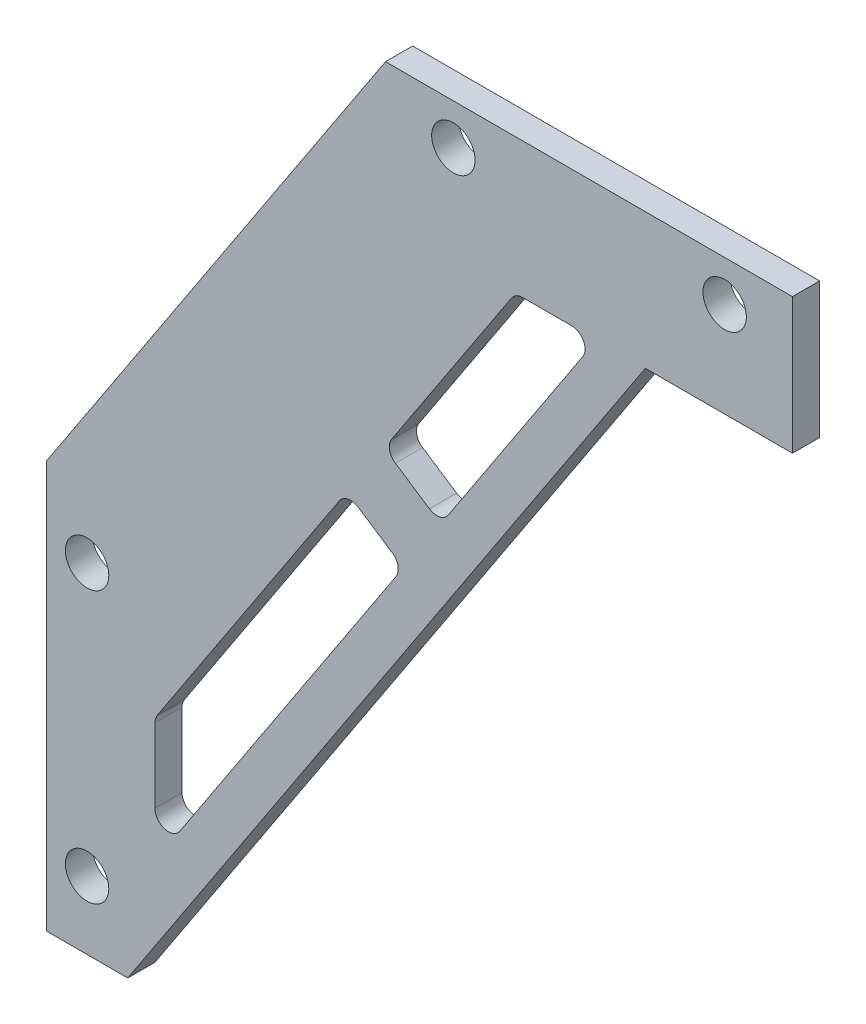
SolidWorks part; units mm, degrees
material "Thornel Mat VMA"
ref_plane "前视基准面" through (0, 0, 0) normal (0, 0, 1) x (1, 0, 0)
ref_plane "上视基准面" through (0, 0, 0) normal (0, 1, 0) x (1, 0, 0)
ref_plane "右视基准面" through (0, 0, 0) normal (1, 0, 0) x (0, 0, -1)
sketch "草图1" plane through (0, 0, 0) normal (0, 0, 1) x (1, 0, 0)
  line L0 (0, 0) -> (0, 30)
  line L1 (0, 30) -> (25, 68)
  line L2 (25, 68) -> (55, 68)
  line L3 (55, 68) -> (55, 58)
  line L4 (55, 58) -> (44.1579, 58)
  line L5 (44.1579, 58) -> (6, 0)
  line L6 (6, 0) -> (0, 0)
  line L7 (3, 25) -> (3, 5) construction
  line L8 (30, 65) -> (50, 65) construction
  circle A0 centre (3, 25) radius 1.6
  circle A1 centre (3, 5) radius 1.6
  circle A2 centre (30, 65) radius 1.6
  circle A3 centre (50, 65) radius 1.6
  dimension "D4" = 20
  dimension "D7" = 3.2
  dimension "D11" = 3.2
  dimension "D1" = 30
  dimension "D2" = 6
  dimension "D3" = 10
  dimension "D5" = 3
  dimension "D6" = 5
  dimension "D8" = 25
  dimension "D9" = 38
  dimension "D10" = 30
  dimension "D12" = 5
  dimension "D13" = 5
  dimension "D14" = 3
extrude "凸台-拉伸1" add sketch "草图1" along normal blind 2
sketch "草图2" plane through (0, 0, 2) normal (0, 0, 1) x (1, 0, 0)
  line L0 (35.121, 58) -> (38.712, 58)
  line L1 (39.5474, 56.4504) -> (29.6216, 41.3632)
  line L2 (8, 11.8378) -> (8, 17.2962)
  line L3 (8.1646, 17.8458) -> (21.5972, 38.2634)
  line L4 (6, 0) -> (44.1579, 58) construction
  line L5 (25.7303, 42.7262) -> (28.2366, 41.0774)
  line L6 (22.9822, 38.5492) -> (25.4885, 36.9003)
  line L7 (25.4445, 44.1113) -> (34.2855, 57.5496)
  line L8 (25.7743, 35.5153) -> (9.8354, 11.2882)
  line L9 (0, 30) -> (0, 0) construction
  arc A0 (38.712, 58) -> (39.5474, 56.4504) centre (38.712, 57) cw
  arc A1 (35.121, 58) -> (34.2855, 57.5496) centre (35.121, 57) ccw
  arc A2 (8, 17.2962) -> (8.1646, 17.8458) centre (9, 17.2962) cw
  arc A3 (9.8354, 11.2882) -> (8, 11.8378) centre (9, 11.8378) cw
  arc A4 (28.2366, 41.0774) -> (29.6216, 41.3632) centre (28.7862, 41.9128) ccw
  arc A5 (25.7303, 42.7262) -> (25.4445, 44.1113) centre (26.2799, 43.5617) cw
  arc A6 (25.4885, 36.9003) -> (25.7743, 35.5153) centre (24.9389, 36.0649) cw
  arc A7 (22.9822, 38.5492) -> (21.5972, 38.2634) centre (22.4326, 37.7137) ccw
  point P24 (24.8949, 43.2759)
  point P27 (26.3239, 36.3507)
  dimension "D3" = 1
  dimension "D6" = 1
  dimension "D1" = 3
  dimension "D2" = 5
  dimension "D4" = 5
  dimension "D5" = 30
  dimension "D7" = 8
extrude "切除-拉伸1" cut sketch "草图2" against normal through all
